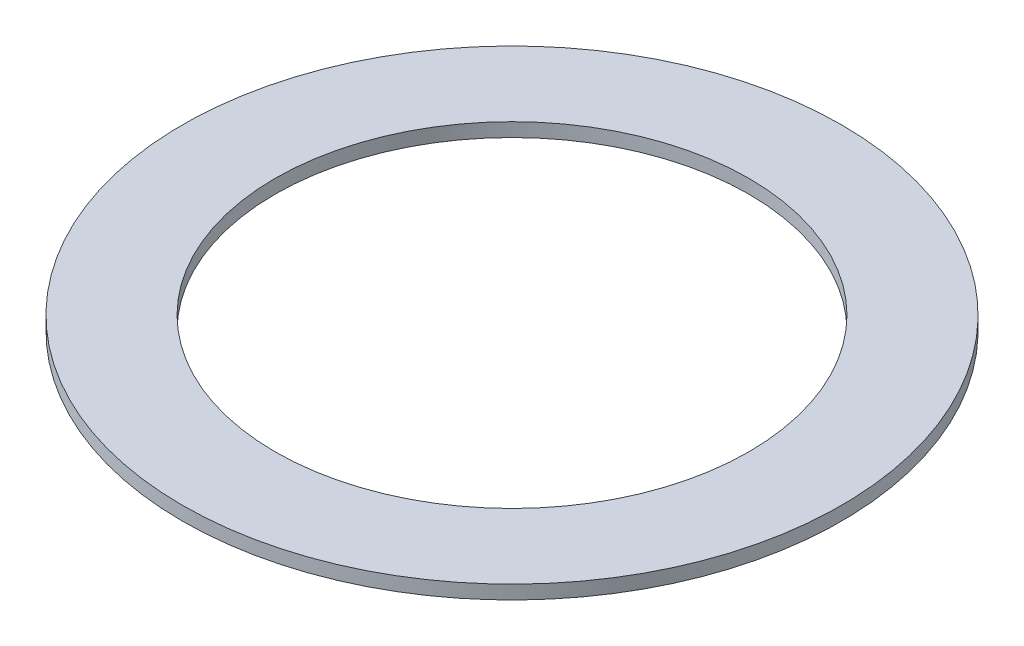
SolidWorks part; units mm, degrees
ref_plane "Front Plane" through (0, 0, 0) normal (0, 0, 1) x (1, 0, 0)
ref_plane "Top Plane" through (0, 0, 0) normal (0, 1, 0) x (1, 0, 0)
ref_plane "Right Plane" through (0, 0, 0) normal (1, 0, 0) x (0, 0, -1)
sketch "Sketch1" plane through (0, 0, 0) normal (0, 1, 0) x (1, 0, 0)
  circle A0 centre (0, 0) radius 8.625
  circle A1 centre (0, 0) radius 12
  dimension "D1" = 17.25
  dimension "D2" = 24
extrude "Boss-Extrude1" add sketch "Sketch1" along normal blind 0.5
